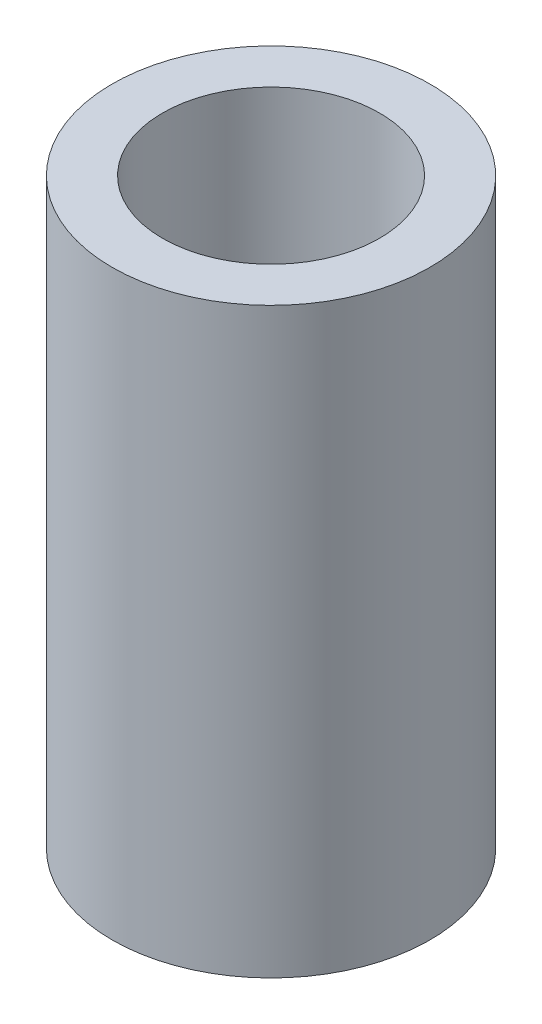
SolidWorks part; units mm, degrees
ref_plane "Front Plane" through (0, 0, 0) normal (0, 0, 1) x (1, 0, 0)
ref_plane "Top Plane" through (0, 0, 0) normal (0, 1, 0) x (1, 0, 0)
ref_plane "Right Plane" through (0, 0, 0) normal (1, 0, 0) x (0, 0, -1)
sketch "Sketch2" plane through (0, 0, 0) normal (0, 1, 0) x (1, 0, 0)
  circle A0 centre (0, 0) radius 6
extrude "Boss-Extrude1" add sketch "Sketch2" along normal blind 22
sketch "Sketch3" plane through (0, 22, 0) normal (0, 1, 0) x (1, 0, 0)
  circle A0 centre (0, 0) radius 4.1
extrude "Cut-Extrude1" cut sketch "Sketch3" against normal blind 10
sketch "Sketch4" plane through (0, 12, 0) normal (0, 1, 0) x (1, 0, 0)
  circle A0 centre (0, 0) radius 2.1
extrude "Cut-Extrude2" cut sketch "Sketch4" against normal blind 10
